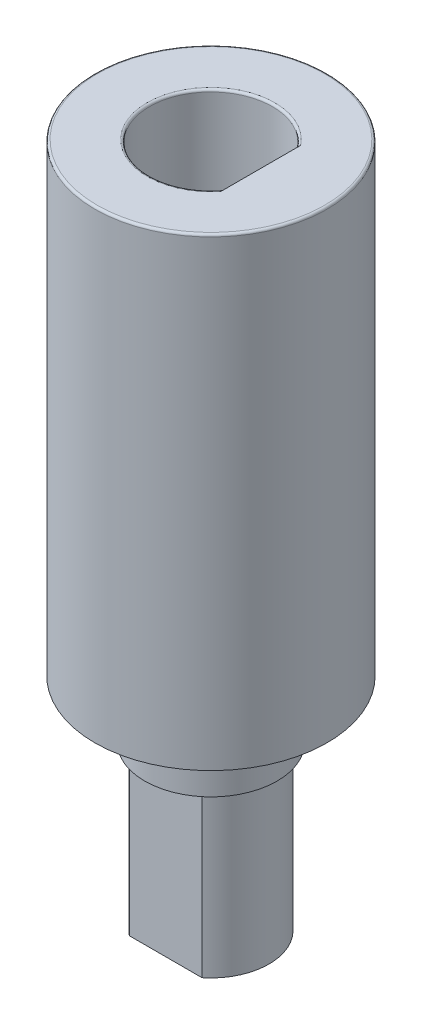
SolidWorks part; units mm, degrees
ref_plane "Front Plane" through (0, 0, 0) normal (0, 0, 1) x (1, 0, 0)
ref_plane "Top Plane" through (0, 0, 0) normal (0, 1, 0) x (1, 0, 0)
ref_plane "Right Plane" through (0, 0, 0) normal (1, 0, 0) x (0, 0, -1)
sketch "Sketch2" plane through (0, 0, 0) normal (0, 1, 0) x (1, 0, 0)
  circle A0 centre (0, 0) radius 5
  dimension "D1" = 10
extrude "Boss-Extrude1" add sketch "Sketch2" along normal blind 20
sketch "Sketch3" plane through (0, 20, 0) normal (0, 1, 0) x (1, 0, 0)
  line L0 (2.15, 1.5492) -> (2.15, -1.5492)
  arc A0 (2.15, 1.5492) -> (2.15, -1.5492) centre (0, 0) ccw
  point P1 (-2.65, 0)
  dimension "D1" = 5.3
  dimension "D2" = 4.8
extrude "Cut-Extrude3" cut sketch "Sketch3" against normal blind 15
sketch "Sketch4" plane through (0, 0, 0) normal (0, -1, 0) x (-1, 0, 0)
  line L1 (1.5644, 1.95) -> (-1.5644, 1.95)
  line L3 (1.5644, -1.95) -> (-1.5644, -1.95)
  line L5 (1.5644, 1.95) -> (-1.5644, -1.95) construction
  line L6 (1.5644, -1.95) -> (-1.5644, 1.95) construction
  arc A0 (1.5644, -1.95) -> (1.5644, 1.95) centre (0, 0) ccw
  arc A1 (-1.5644, -1.95) -> (-1.5644, 1.95) centre (0, 0) cw
  circle A2 centre (0, 0) radius 2.5 construction
  point P0 (0, 0)
  dimension "D1" = 5
  dimension "D2" = 3.9
extrude "Boss-Extrude2" add sketch "Sketch4" along normal blind 9.5
sketch "Sketch6" plane through (0, 0, 0) normal (0, -1, 0) x (1, 0, 0)
  circle A0 centre (0, 0) radius 2.85
  dimension "D1" = 5.7
extrude "Boss-Extrude3" add sketch "Sketch6" along normal blind 2.5
fillet "Fillet3" radius 0.1 2 edges at (0, 20, 5) (-2.65, 20, 0)
